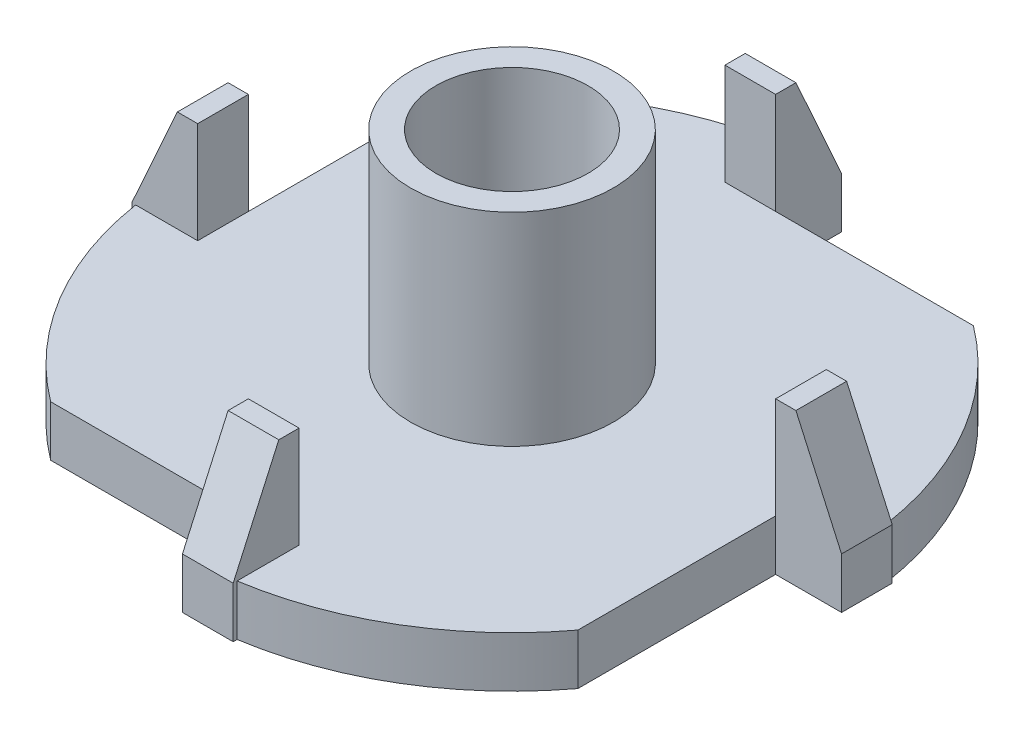
SolidWorks part; units mm, degrees
material "Stainless Steel (ferritic)"
ref_plane "Front Plane" through (0, 0, 0) normal (0, 0, 1) x (1, 0, 0)
ref_plane "Top Plane" through (0, 0, 0) normal (0, 1, 0) x (1, 0, 0)
ref_plane "Right Plane" through (0, 0, 0) normal (1, 0, 0) x (0, 0, -1)
sketch "Sketch1" plane through (0, 0, 0) normal (0, 1, 0) x (1, 0, 0)
  line L0 (-5.2, 3.9) -> (-5.2, 0)
  line L1 (-5.2, 0) -> (-6.5, 0)
  line L2 (0, 5.2) -> (0, 6.5)
  line L3 (3.9, 5.2) -> (0, 5.2)
  line L4 (5.2, 0) -> (6.5, 0)
  line L5 (5.2, -3.9) -> (5.2, 0)
  line L6 (0, -5.2) -> (0, -6.5)
  line L7 (-3.9, -5.2) -> (0, -5.2)
  line L8 (-6.5, 0) -> (-6.5, -1)
  line L9 (-6.5, -1) -> (-6.4226, -1)
  line L10 (0, 6.5) -> (-1, 6.5)
  line L11 (-1, 6.5) -> (-1, 6.4226)
  line L12 (6.5, 0) -> (6.5, 1)
  line L13 (6.5, 1) -> (6.4226, 1)
  line L14 (0, -6.5) -> (1, -6.5)
  line L15 (1, -6.5) -> (1, -6.4226)
  arc A0 (-6.4226, -1) -> (-3.9, -5.2) centre (0, 0) ccw
  circle A1 centre (0, 0) radius 1.5
  arc A2 (-1, 6.4226) -> (-5.2, 3.9) centre (0, 0) ccw
  arc A3 (6.4226, 1) -> (3.9, 5.2) centre (0, 0) ccw
  arc A4 (1, -6.4226) -> (5.2, -3.9) centre (0, 0) ccw
  dimension "D1" = 3
  dimension "D2" = 13
  dimension "D3" = 5.2
  dimension "D5" = 1
  dimension "D4" = 4
  dimension "D6" = 4
extrude "Boss-Extrude1" add sketch "Sketch1" along normal blind 1
cosmetic thread "Cosmetic Thread1" parameters "D2"=4
sketch "Sketch3" plane through (0, 0, 0) normal (-1, 0, 0) x (0, 0, 1)
  line L0 (5.2, 1) -> (5.2, 3)
  line L1 (5.2, 3) -> (5.6, 3)
  line L4 (5.2, 1) -> (6.5, 1)
  line L5 (5.2, 1) -> (6.5, 1) construction
  line L6 (6.5, 1) -> (6.5, 0) construction
  line L7 (6.5, 1) -> (5.6, 3)
  dimension "D1" = 2
  dimension "D2" = 0.4
extrude "Boss-Extrude2" add sketch "Sketch3" against normal blind 1
pattern_circular "CirPattern1" count 4 over 360 about axis through (0, 0, 0) along (0, 1, 0) of "Boss-Extrude2"
sketch "Sketch4" plane through (0, 1, 0) normal (0, 1, 0) x (1, 0, 0)
  circle A0 centre (0, 0) radius 1.5
  circle A1 centre (0, 0) radius 2
  dimension "D1" = 4
extrude "Boss-Extrude3" add sketch "Sketch4" along normal blind 4
